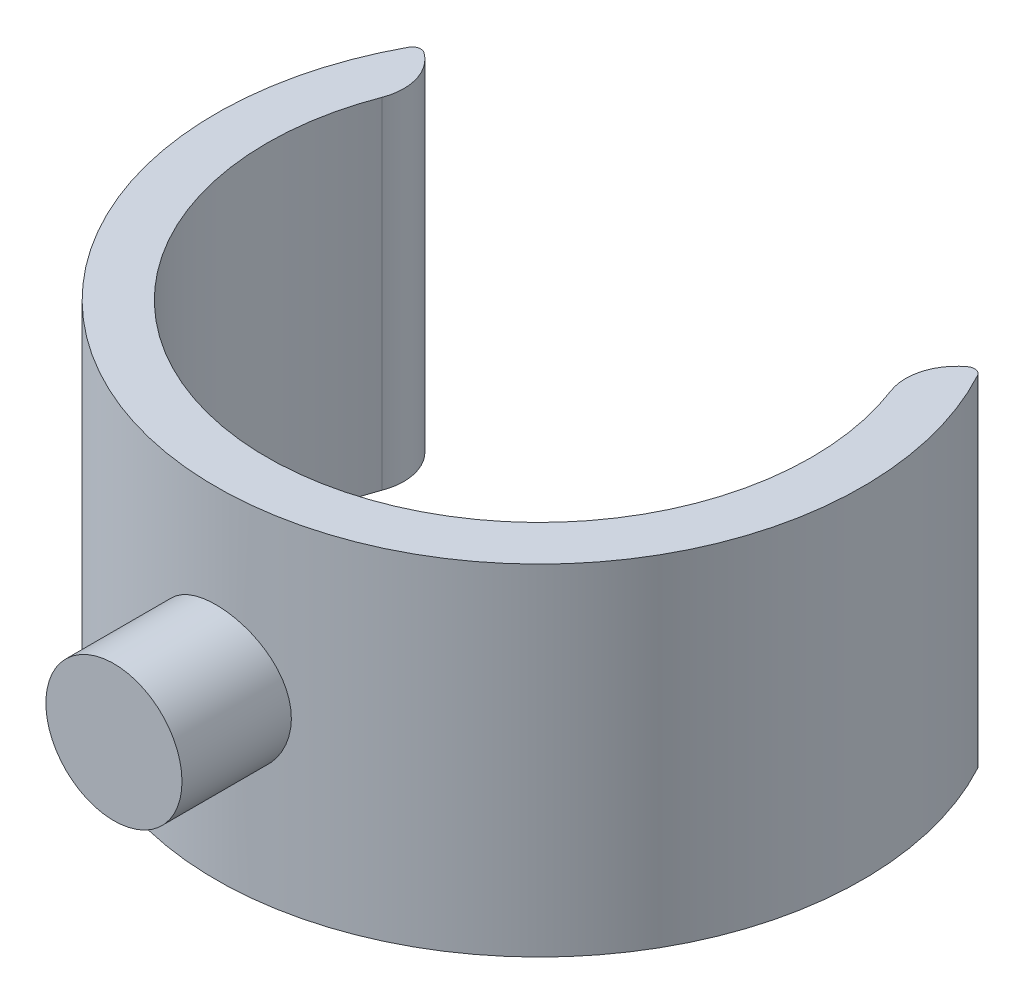
SolidWorks part; units mm, degrees
ref_plane "Alzado" through (0, 0, 0) normal (0, 0, 1) x (1, 0, 0)
ref_plane "Planta" through (0, 0, 0) normal (0, 1, 0) x (1, 0, 0)
ref_plane "Vista lateral" through (0, 0, 0) normal (1, 0, 0) x (0, 0, -1)
sketch "Croquis1" plane through (0, 0, 0) normal (0, 1, 0) x (1, 0, 0)
  line L0 (0, 0) -> (0, 40) construction
  line L1 (0, 0) -> (16.4545, 9.5)
  line L2 (0, 0) -> (-16.4545, 9.5)
  arc A0 (-16.4545, 9.5) -> (16.4545, 9.5) centre (0, 0) ccw
  arc A1 (-13.8564, 8) -> (13.8564, 8) centre (0, 0) ccw
  circle A3 centre (0, 0) radius 16 construction
  circle A4 centre (0, 0) radius 19 construction
  point P3 (38.2522, 11.6949)
  point P8 (37, 0)
  dimension "D1" = 38
  dimension "D3" = 60
  dimension "D2" = 3
extrude "Extruir1" add sketch "Croquis1" along normal blind 20 contours A1 L2 A0 L1
sketch "Croquis2" plane through (0, 0, 0) normal (0, 0, 1) x (1, 0, 0)
  line L0 (0, 0) -> (0, 20) construction
  line L1 (19, 20) -> (-19, 20) construction
  circle A0 centre (0, 10) radius 4
  dimension "D1" = 8
extrude "Extruir2" add sketch "Croquis2" against normal up to surface (6.4258 mm away) from offset 25
fillet "Redondeo1" radius 3 2 edges at (-13.8564, 10, -8) (13.8564, 10, -8)
fillet "Redondeo2" radius 0.5 2 edges at (16.4545, 10, -9.5) (-16.4545, 10, -9.5)
